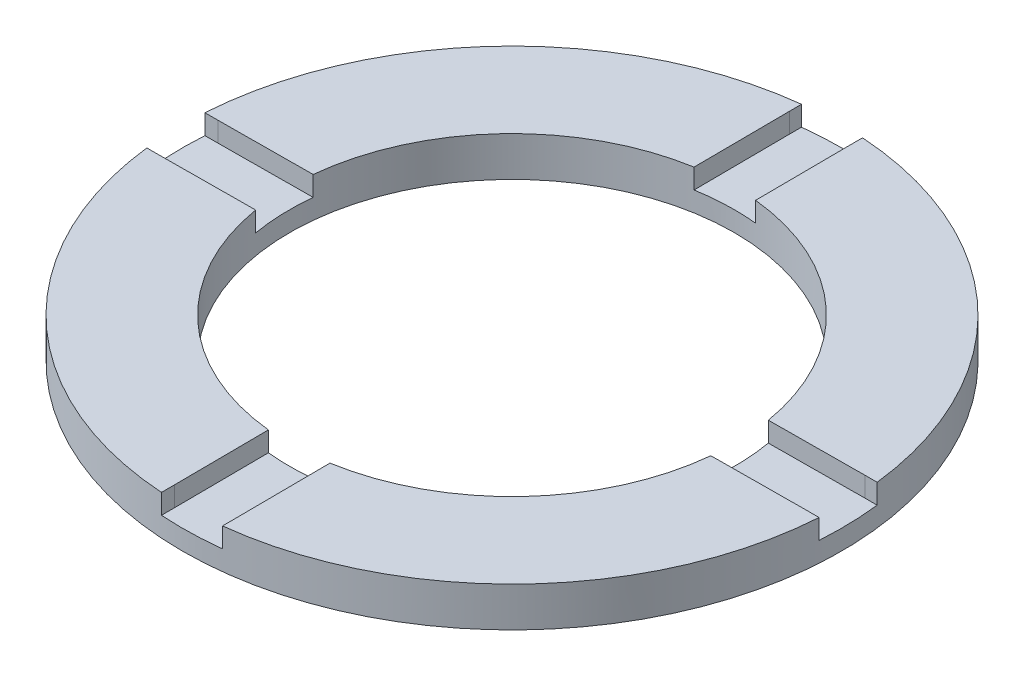
SolidWorks part; units mm, degrees
ref_plane "Front Plane" through (0, 0, 0) normal (0, 0, 1) x (1, 0, 0)
ref_plane "Top Plane" through (0, 0, 0) normal (0, 1, 0) x (1, 0, 0)
ref_plane "Right Plane" through (0, 0, 0) normal (1, 0, 0) x (0, 0, -1)
sketch "Sketch1" plane through (0, 0, 0) normal (0, 1, 0) x (1, 0, 0)
  circle A0 centre (0, 0) radius 83
  dimension "D1" = 166
extrude "Boss-Extrude1" add sketch "Sketch1" along normal blind 10
sketch "Sketch3" plane through (0, 0, 0) normal (0, -1, 0) x (1, 0, 0)
  circle A0 centre (0, 0) radius 56
extrude "Cut-Extrude2" cut sketch "Sketch3" against normal through all
sketch "Sketch6" plane through (0, 10, 0) normal (0, 1, 0) x (1, 0, 0)
  line L0 (55.7154, -5.6383) -> (79.5398, -5.4759) construction
  line L1 (-79.4319, -9.5237) -> (-55.2125, -9.3586) construction
  line L2 (79.4319, 9.5237) -> (55.2125, 9.3586) construction
  line L7 (5.6383, 55.7154) -> (5.4759, 79.5398) construction
  line L8 (-9.5237, 79.4319) -> (-9.3586, 55.2125) construction
  line L9 (55.7154, -5.6383) -> (79.5398, -5.4759)
  line L10 (79.4319, 9.5237) -> (55.2125, 9.3586)
  line L15 (5.6383, 55.7154) -> (5.4759, 79.5398)
  line L16 (-9.5237, 79.4319) -> (-9.3586, 55.2125)
  line L17 (79.4319, 9.5237) -> (82.4518, 9.5237)
  line L18 (79.5398, -5.4759) -> (82.8192, -5.4759)
  line L19 (-55.7154, 5.6383) -> (-79.5398, 5.4759) construction
  line L20 (-79.4319, -9.5237) -> (-55.2125, -9.3586)
  line L21 (-55.7154, 5.6383) -> (-79.5398, 5.4759)
  line L22 (9.5237, -79.4319) -> (9.3586, -55.2125) construction
  line L23 (-9.5237, 79.4319) -> (-9.5237, 82.4518)
  line L24 (5.4759, 79.5398) -> (5.4759, 82.8192)
  line L25 (-5.6383, -55.7154) -> (-5.4759, -79.5398) construction
  line L26 (9.5237, -79.4319) -> (9.3586, -55.2125)
  line L27 (-5.6383, -55.7154) -> (-5.4759, -79.5398)
  line L28 (-79.5398, 5.4759) -> (-82.8192, 5.4759)
  line L29 (-79.4319, -9.5237) -> (-82.4518, -9.5237)
  line L30 (-5.4759, -79.5398) -> (-5.4759, -82.8192)
  line L31 (9.5237, -79.4319) -> (9.5237, -82.4518)
  arc A0 (5.4759, 82.8192) -> (-9.5237, 82.4518) centre (0, 0) ccw
  arc A1 (-5.6383, -55.7154) -> (9.3586, -55.2125) centre (0, 0) ccw
  circle A2 centre (0, 0) radius 83 construction
  arc A3 (82.8192, -5.4759) -> (82.4518, 9.5237) centre (0, 0) ccw
  arc A4 (-9.3586, 55.2125) -> (5.6383, 55.7154) centre (0, 0) cw
  arc A5 (55.2125, 9.3586) -> (55.7154, -5.6383) centre (0, 0) cw
  arc A6 (-55.7154, 5.6383) -> (-55.2125, -9.3586) centre (0, 0) ccw
  arc A7 (-5.4759, -82.8192) -> (9.5237, -82.4518) centre (0, 0) ccw
  arc A8 (-82.8192, 5.4759) -> (-82.4518, -9.5237) centre (0, 0) ccw
  arc A9 (82.8192, -5.4759) -> (-9.5237, 82.4518) centre (0, 0) ccw
extrude "Cut-Extrude4" cut sketch "Sketch6" against normal blind 5 contours L21 L28 A8 L29 L20 A6 | A7 L31 L26 A1 L27 L30 | A5 L9 L18 A3 L17 L10 | A4 L15 L24 A0 L23 L16
